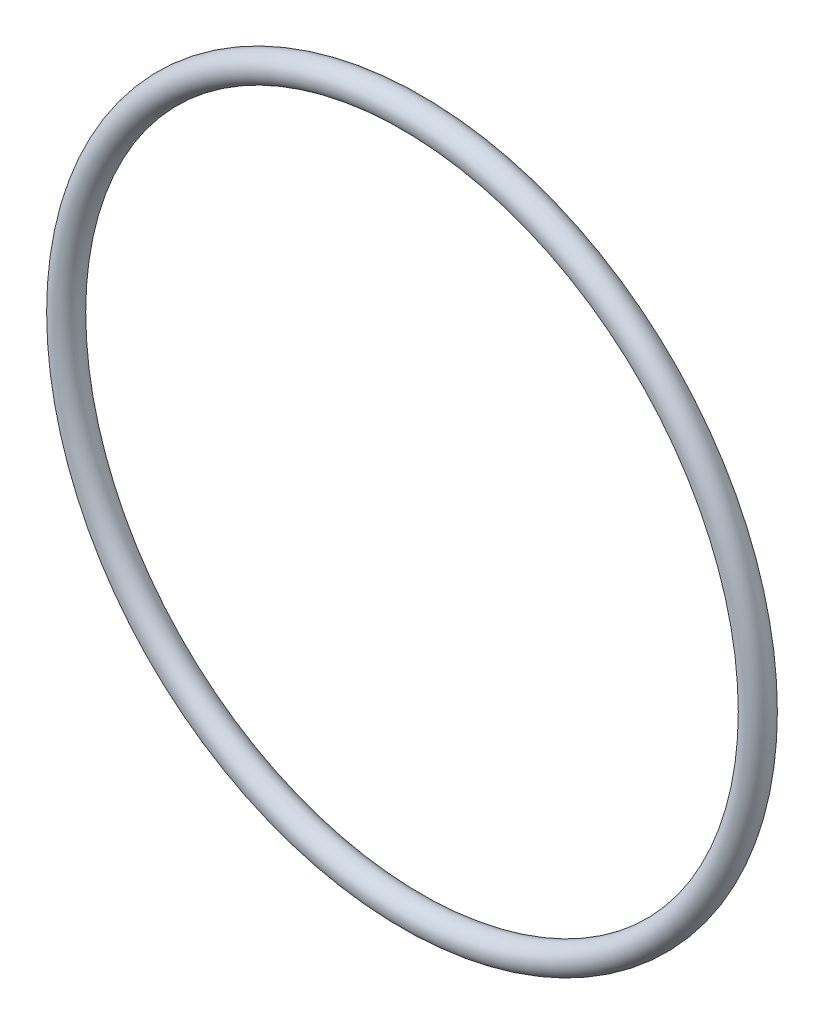
SolidWorks part; units mm, degrees
material "NBR"
ref_plane "Front Plane" through (0, 0, 0) normal (0, 0, 1) x (1, 0, 0)
ref_plane "Top Plane" through (0, 0, 0) normal (0, 1, 0) x (1, 0, 0)
ref_plane "Right Plane" through (0, 0, 0) normal (1, 0, 0) x (0, 0, -1)
sketch "Sketch1" plane through (0, 0, 0) normal (0, 0, 1) x (1, 0, 0)
  line L0 (-13, 0) -> (13, 0) construction
  circle A0 centre (0, 0) radius 13
  circle A1 centre (0, 0) radius 12
  point P4 (12, 0)
  point P5 (13, 0)
  point P8 (0, 0)
  dimension "ID" = 24
  dimension "Width" = 1
  dimension "OD" = 26
sketch "Sketch2" plane through (0, 0, 0) normal (0, 1, 0) x (1, 0, 0)
  line L0 (-13, 0) -> (13, 0) construction
  line L1 (0, 0.5) -> (0, -0.5) construction
  circle A0 centre (12.5, 0) radius 0.5
  point P8 (0, 0)
  point P11 (12.5, 0.5)
revolve "Revolve1" add sketch "Sketch2" angle 360 about L1
sketch "Sketch3" plane through (0, 0, 0) normal (1, 0, 0) x (0, 0, -1)
  line L0 (-0.5, 0) -> (0.5, 0) construction
  line L1 (0.5, -12.5) -> (0.5, 12.5) construction
  point P2 (0, 0)
